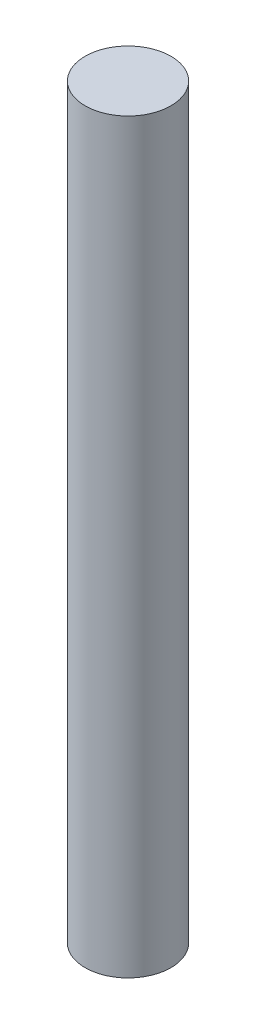
SolidWorks part; units mm, degrees
ref_plane "Front Plane" through (0, 0, 0) normal (0, 0, 1) x (1, 0, 0)
ref_plane "Top Plane" through (0, 0, 0) normal (0, 1, 0) x (1, 0, 0)
ref_plane "Right Plane" through (0, 0, 0) normal (1, 0, 0) x (0, 0, -1)
sketch "Sketch1" plane through (0, 0, 0) normal (0, 1, 0) x (1, 0, 0)
  circle A0 centre (0, 0) radius 1.4605
  dimension "D1" = 2.921
extrude "Boss-Extrude1" add sketch "Sketch1" along normal blind 25.4
